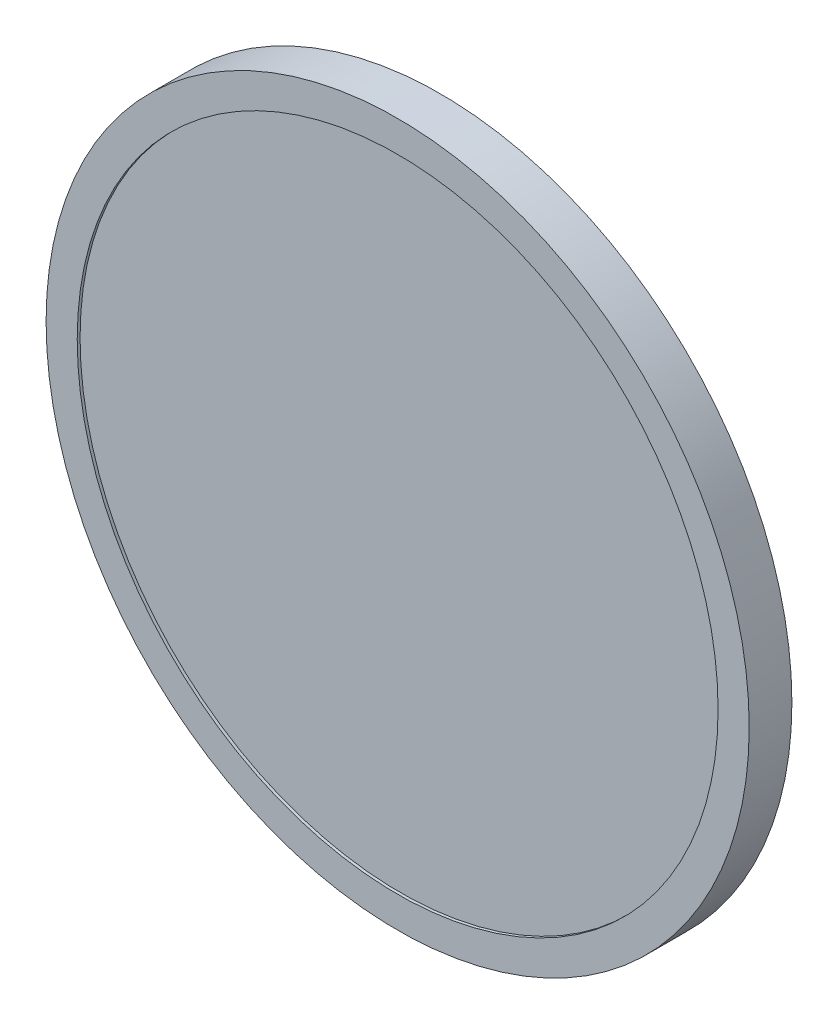
SolidWorks part; units mm, degrees
ref_plane "Front Plane" through (0, 0, 0) normal (0, 0, 1) x (1, 0, 0)
ref_plane "Top Plane" through (0, 0, 0) normal (0, 1, 0) x (1, 0, 0)
ref_plane "Right Plane" through (0, 0, 0) normal (1, 0, 0) x (0, 0, -1)
sketch "Sketch1" plane through (0, 0, 0) normal (0, 0, 1) x (1, 0, 0)
  circle A0 centre (0, 0) radius 31.369
  dimension "D1" = 62.738
extrude "Boss-Extrude1" add sketch "Sketch1" along normal blind 3.81 contours A0
sketch "Sketch2" plane through (0, 0, 3.81) normal (0, 0, 1) x (1, 0, 0)
  circle A0 centre (0, 0) radius 28.5916
extrude "Cut-Extrude2" cut sketch "Sketch2" against normal blind 0.254 contours A0
